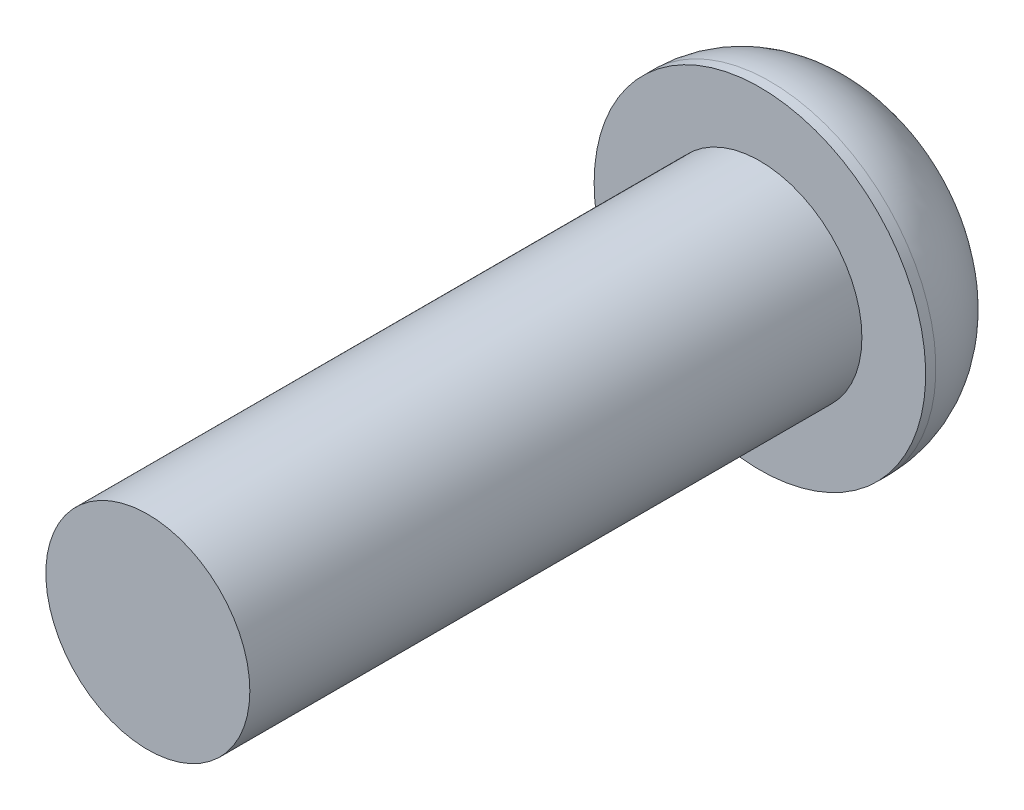
SolidWorks part; units mm, degrees
ref_plane "前视基准面" through (0, 0, 0) normal (0, 0, 1) x (1, 0, 0)
ref_plane "上视基准面" through (0, 0, 0) normal (0, 1, 0) x (1, 0, 0)
ref_plane "右视基准面" through (0, 0, 0) normal (1, 0, 0) x (0, 0, -1)
sketch "草图1" plane through (0, 0, 0) normal (0, 0, 1) x (1, 0, 0)
  circle A0 centre (0, 0) radius 2
  dimension "D1" = 4
extrude "凸台-拉伸1" add sketch "草图1" along normal blind 12
sketch "草图2" plane through (0, 0, 0) normal (0, 0, -1) x (-1, 0, 0)
  circle A0 centre (0, 0) radius 3.25
  dimension "D1" = 6.5
extrude "凸台-拉伸2" add sketch "草图2" along normal blind 2.2
fillet "圆角1" radius 2 1 edges at (-3.25, 0, -2.2)
sketch "草图3" plane through (0, 0, -2.2) normal (0, 0, -1) x (-1, 0, 0)
  line L0 (0, 3.24) -> (0, -3.24) construction
  line L1 (-3.24, 0) -> (3.24, 0) construction
  line L2 (-3.24, 0.25) -> (3.24, 0.25) construction
  line L3 (0.25, 3.24) -> (0.25, -3.24) construction
  line L4 (-3.24, -0.25) -> (3.24, -0.25) construction
  line L5 (-0.25, 3.24) -> (-0.25, -3.24) construction
  line L7 (3.24, 0.25) -> (3.24, -0.25)
  line L8 (-0.25, 3.24) -> (0.25, 3.24)
  line L10 (-0.25, 3.24) -> (-0.25, 0.25)
  line L11 (0.25, 3.24) -> (0.25, 0.25)
  line L12 (3.24, 0.25) -> (0.25, 0.25)
  line L13 (3.24, -0.25) -> (0.25, -0.25)
  line L15 (0.25, -3.24) -> (0.25, -0.25)
  line L16 (-0.25, -3.24) -> (-0.25, -0.25)
  line L17 (0.25, -3.24) -> (-0.25, -3.24)
  line L18 (-3.24, -0.25) -> (-0.25, -0.25)
  line L19 (-3.24, 0.25) -> (-0.25, 0.25)
  line L20 (-3.24, -0.25) -> (-3.24, 0.25)
  line L21 (3.24, 0.25) -> (3.24, -0.25) [skipped]
  circle A1 centre (0, 0) radius 3.24 construction
  dimension "D1" = 0.25
  dimension "D2" = 0.25
  dimension "D3" = 4
extrude "切除-拉伸1" cut sketch "草图3" against normal blind 0.5
